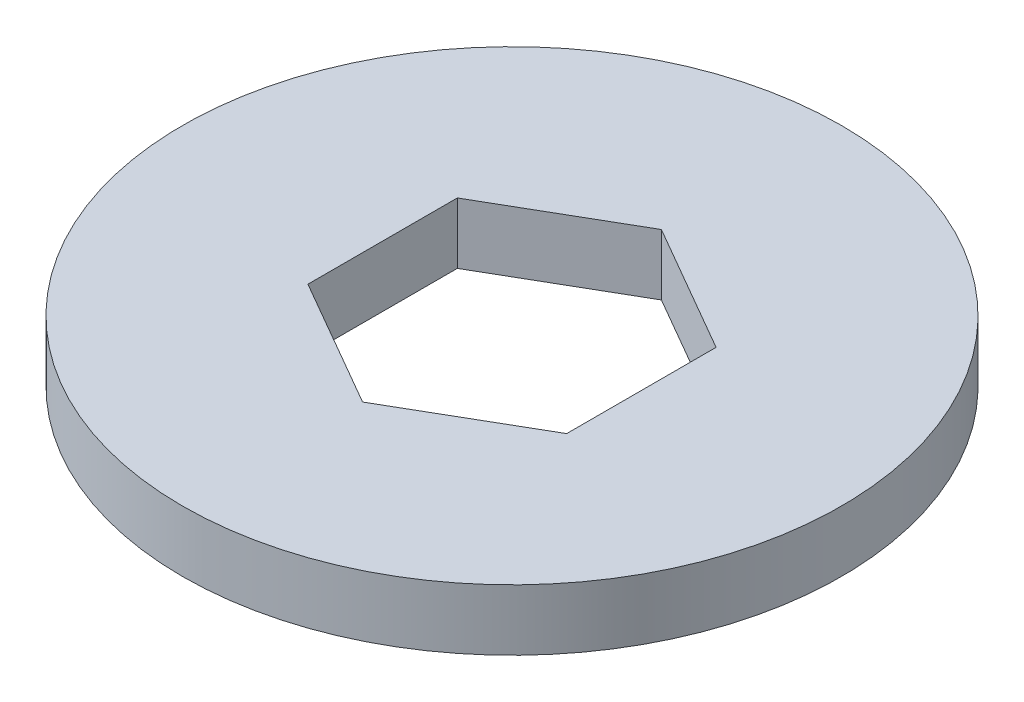
SolidWorks part; units mm, degrees
ref_plane "前视基准面" through (0, 0, 0) normal (0, 0, 1) x (1, 0, 0)
ref_plane "上视基准面" through (0, 0, 0) normal (0, 1, 0) x (1, 0, 0)
ref_plane "右视基准面" through (0, 0, 0) normal (1, 0, 0) x (0, 0, -1)
other "Configuration Table"
sketch "草图1" plane through (0, 0, 0) normal (0, 1, 0) x (1, 0, 0)
  line L1 (0, -6.1199) -> (5.3, -3.06)
  line L2 (5.3, -3.06) -> (5.3, 3.06)
  line L3 (5.3, 3.06) -> (0, 6.1199)
  line L4 (0, 6.1199) -> (-5.3, 3.06)
  line L5 (-5.3, 3.06) -> (-5.3, -3.06)
  line L6 (-5.3, -3.06) -> (0, -6.1199)
  circle A0 centre (0, 0) radius 5.3 construction
  circle A1 centre (0, 0) radius 13.5
  dimension "D2" = 27
  dimension "D1" = 10.6
extrude "凸台-拉伸1" add sketch "草图1" along normal blind 2.5
